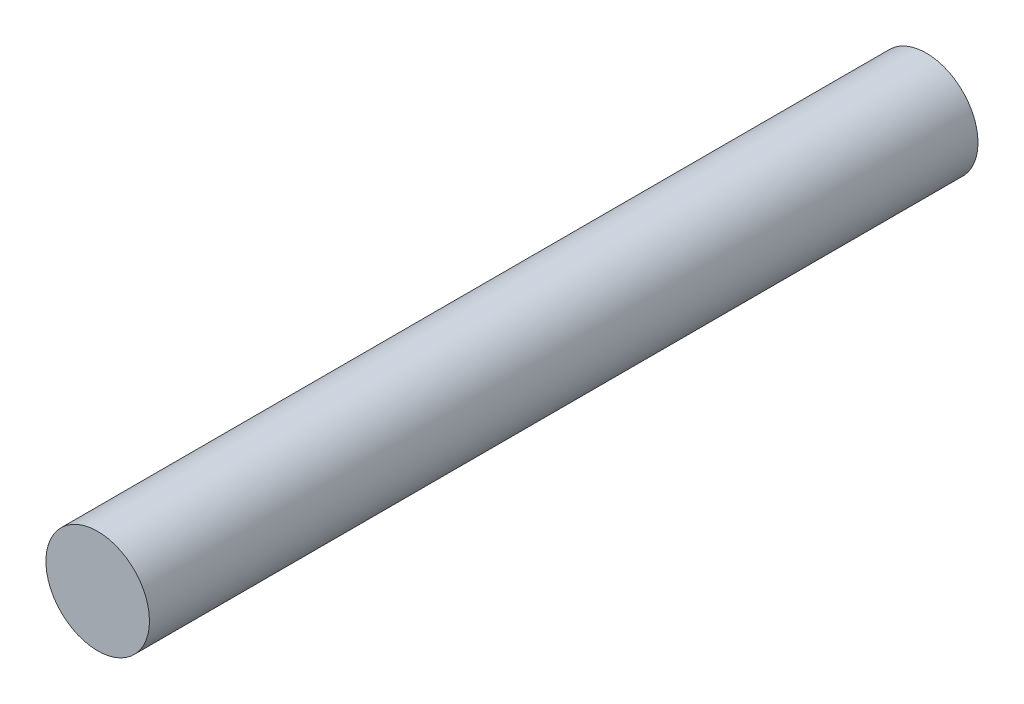
SolidWorks part; units mm, degrees
ref_plane "Front Plane" through (0, 0, 0) normal (0, 0, 1) x (1, 0, 0)
ref_plane "Top Plane" through (0, 0, 0) normal (0, 1, 0) x (1, 0, 0)
ref_plane "Right Plane" through (0, 0, 0) normal (1, 0, 0) x (0, 0, -1)
sketch "Sketch1" plane through (0, 0, 0) normal (0, 0, 1) x (1, 0, 0)
  circle A0 centre (0, 0) radius 1.5875
  dimension "D1" = 3.175
extrude "Boss-Extrude1" add sketch "Sketch1" along normal blind 25.4 contours A0
equation "\"Tout\"= 1.25"
equation "\"Gear ratio\"= 24 / 9"
equation "\"Tinpu\"= 1.25 / \"Gear ratio\""
equation "\"shear stress\" = ( 5.1 * \"Tinpu\" ) / ( .001953 )"
equation "\"L\"= 1"
equation "\"D\"= .125"
equation "\"D1@Sketch1\"=\"D\""
equation "\"D1@Boss-Extrude1\"=\"L\""
